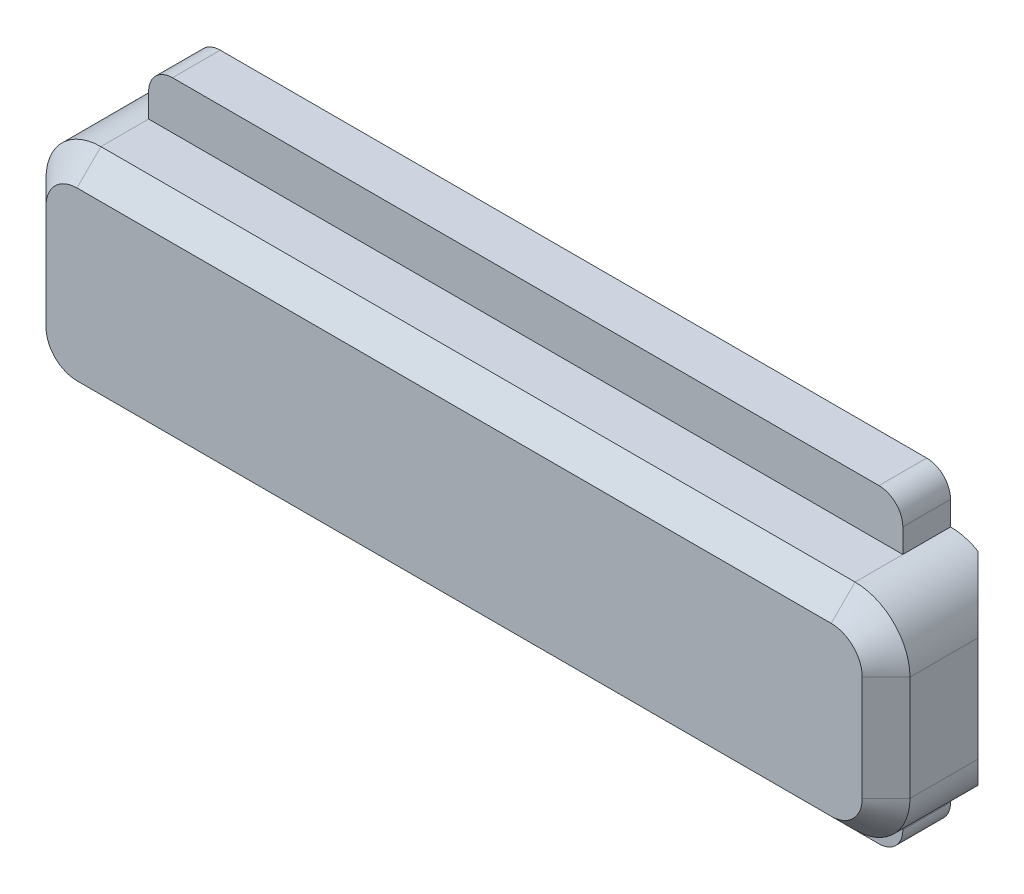
SolidWorks part; units mm, degrees
ref_plane "前视基准面" through (0, 0, 0) normal (0, 0, 1) x (1, 0, 0)
ref_plane "上视基准面" through (0, 0, 0) normal (0, 1, 0) x (1, 0, 0)
ref_plane "右视基准面" through (0, 0, 0) normal (1, 0, 0) x (0, 0, -1)
sketch "草图1" plane through (0, 0, 0) normal (0, 0, 1) x (1, 0, 0)
  line L3 (-9.15, -1.25) -> (-9.15, -3.45) construction
  line L4 (7.9, 0) -> (-7.9, 0) construction
  line L5 (9.15, -3.45) -> (9.15, -1.25) construction
  line L6 (-7.9, -4.7) -> (7.9, -4.7) construction
  line L7 (-9.05, -1.25) -> (-9.05, -3.45)
  line L8 (-7.9, -4.6) -> (7.9, -4.6)
  line L9 (9.05, -3.45) -> (9.05, -1.25)
  line L10 (7.9, -0.1) -> (-7.9, -0.1)
  arc A2 (-7.9, 0) -> (-9.15, -1.25) centre (-7.9, -1.25) ccw construction
  arc A3 (9.15, -1.25) -> (7.9, 0) centre (7.9, -1.25) ccw construction
  arc A4 (9.15, -3.45) -> (7.9, -4.7) centre (7.9, -3.45) cw construction
  arc A5 (-7.9, -4.7) -> (-9.15, -3.45) centre (-7.9, -3.45) cw construction
  arc A6 (-7.9, -4.6) -> (-9.05, -3.45) centre (-7.9, -3.45) cw
  arc A7 (9.05, -3.45) -> (7.9, -4.6) centre (7.9, -3.45) cw
  arc A8 (9.05, -1.25) -> (7.9, -0.1) centre (7.9, -1.25) ccw
  arc A9 (-7.9, -0.1) -> (-9.05, -1.25) centre (-7.9, -1.25) ccw
  dimension "D1" = 1.25
  dimension "D2" = 0.1
extrude "凸台-拉伸1" add sketch "草图1" against normal blind 2.5
sketch "草图2" plane through (0, 0, -2.5) normal (0, 0, -1) x (-1, 0, 0)
  line L0 (0, -0.1) -> (0, -4.6) construction
  line L1 (-7.9, -0.1) -> (7.9, -0.1) construction
  line L2 (7.9, -4.6) -> (-7.9, -4.6) construction
  line L4 (-7.9, 0.9) -> (7.9, 0.9)
  line L5 (-7.9, 0.9) -> (-7.9, -5.6)
  line L6 (-7.9, -5.6) -> (7.9, -5.6)
  line L7 (7.9, 0.9) -> (7.9, -5.6)
  line L8 (-7.9, 0.9) -> (7.9, -5.6) construction
  line L9 (-7.9, -5.6) -> (7.9, 0.9) construction
  point P6 (0, -2.35)
  dimension "D1" = 1
extrude "凸台-拉伸2" add sketch "草图2" against normal blind 1
fillet "圆角1" radius 0.5 4 edges at (-7.9, 0.9, -2) (7.9, 0.9, -2) (-7.9, -5.6, -2) (7.9, -5.6, -2)
chamfer "倒角1" distance 0.5 angle 45 8 edges at (-8.7132, -4.2632, 0) (0, -4.6, 0) (-9.05, -2.35, 0) (8.7132, -4.2632, 0) (-8.7132, -0.4368, 0) (9.05, -2.35, 0) (0, -0.1, 0) (8.7132, -0.4368, 0)
sketch "草图3" plane through (0, 0.9, 0) normal (0, 1, 0) x (1, 0, 0)
  line L0 (8.475, 2.5) -> (9.05, 1.925)
  line L1 (9.05, 1.925) -> (9.05, 2.5)
  line L2 (9.05, 2.5) -> (8.475, 2.5)
  line L3 (0, 0) -> (0, 4.9184) construction
  line L5 (9.05, 2.5) -> (9.05, 0.5) construction
  line L6 (-9.05, 1.925) -> (-9.05, 2.5)
  line L7 (-8.475, 2.5) -> (-9.05, 1.925)
  line L8 (-9.05, 2.5) -> (-8.475, 2.5)
  line L9 (9.05, 2.5) -> (7.9, 2.5) construction
  dimension "D1" = 45
extrude "切除-拉伸1" cut sketch "草图3" against normal through all
